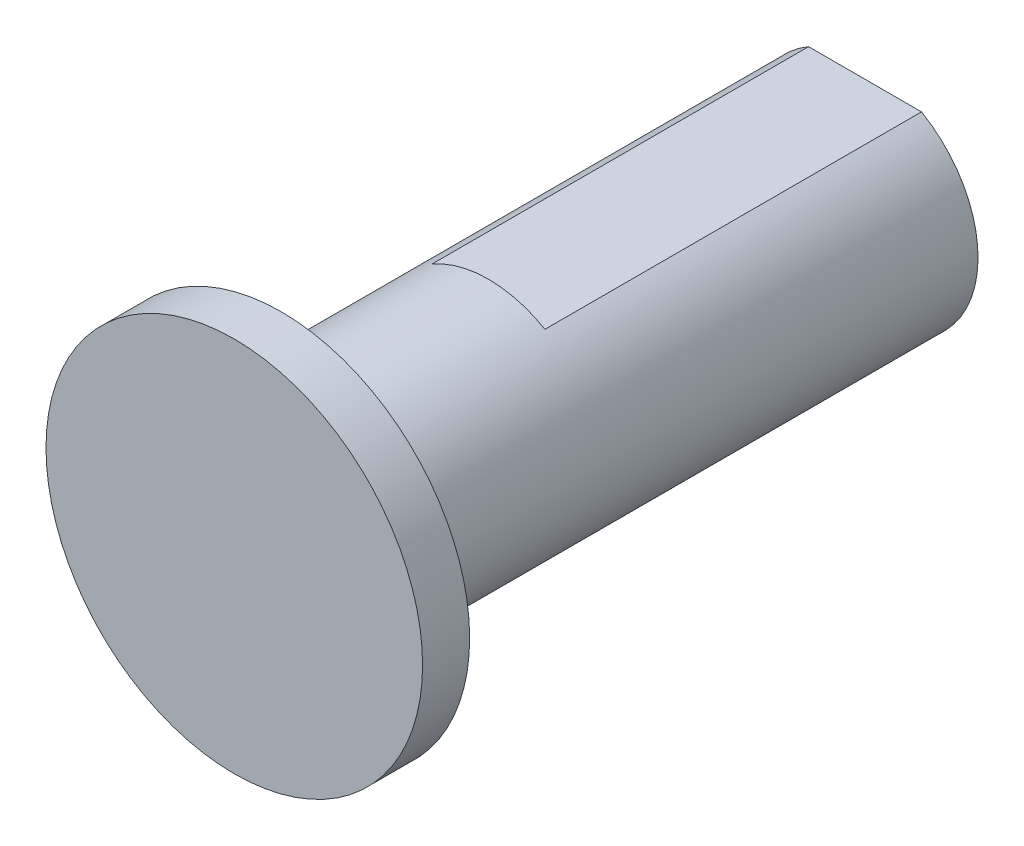
SolidWorks part; units mm, degrees
ref_plane "Front Plane" through (0, 0, 0) normal (0, 0, 1) x (1, 0, 0)
ref_plane "Top Plane" through (0, 0, 0) normal (0, 1, 0) x (1, 0, 0)
ref_plane "Right Plane" through (0, 0, 0) normal (1, 0, 0) x (0, 0, -1)
sketch "Sketch1" plane through (0, 0, 0) normal (0, 0, 1) x (1, 0, 0)
  line L0 (-3, 5.1962) -> (3, 5.1962)
  circle A0 centre (0, 0) radius 6
  dimension "D1" = 12
  dimension "D2" = 6
extrude "Boss-Extrude1" add sketch "Sketch1" along normal blind 31 contours A0
sketch "Sketch2" plane through (0, 0, 0) normal (0, 0, -1) x (-1, 0, 0)
  line L0 (-3, 5.1962) -> (3, 5.1962)
  circle A1 centre (0, 0) radius 6 construction
  circle A2 centre (0, 0) radius 6
  circle M3 centre (0, 0) radius 6
  dimension "D1" = 6
extrude "Cut-Extrude1" cut sketch "Sketch2" against normal blind 20 contours L0 M3
sketch "Sketch3" plane through (0, 0, 31) normal (0, 0, 1) x (1, 0, 0)
  circle A0 centre (0, 0) radius 10
  dimension "D1" = 20
extrude "Boss-Extrude2" add sketch "Sketch3" along normal blind 2.5
